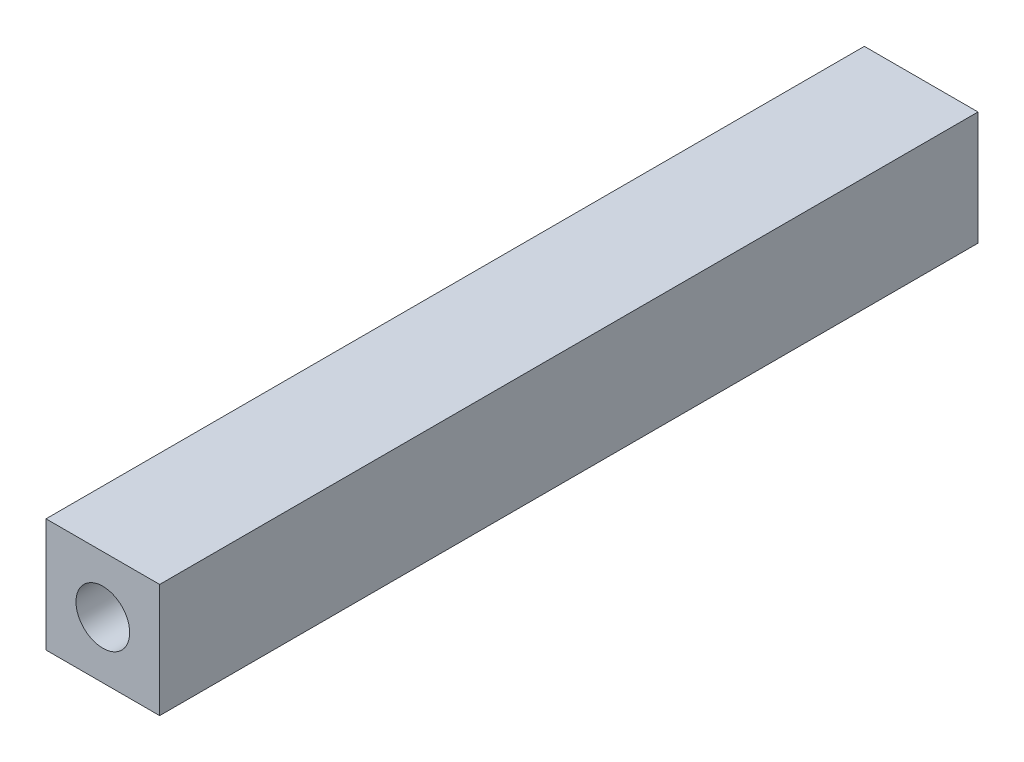
SolidWorks part; units mm, degrees
ref_plane "Front Plane" through (0, 0, 0) normal (0, 0, 1) x (1, 0, 0)
ref_plane "Top Plane" through (0, 0, 0) normal (0, 1, 0) x (1, 0, 0)
ref_plane "Right Plane" through (0, 0, 0) normal (1, 0, 0) x (0, 0, -1)
sketch "Sketch1" plane through (0, 0, 0) normal (0, 0, 1) x (1, 0, 0)
  line L1 (3.175, -3.175) -> (-3.175, -3.175)
  line L2 (3.175, -3.175) -> (3.175, 3.175)
  line L3 (3.175, 3.175) -> (-3.175, 3.175)
  line L4 (-3.175, -3.175) -> (-3.175, 3.175)
  line L5 (3.175, -3.175) -> (-3.175, 3.175) construction
  line L6 (3.175, 3.175) -> (-3.175, -3.175) construction
  circle A0 centre (0, 0) radius 1.5
  point P0 (0, 0)
  dimension "D3" = 3
  dimension "D1" = 6.35
  dimension "D2" = 6.35
extrude "Boss-Extrude1" add sketch "Sketch1" along normal blind 45.72
